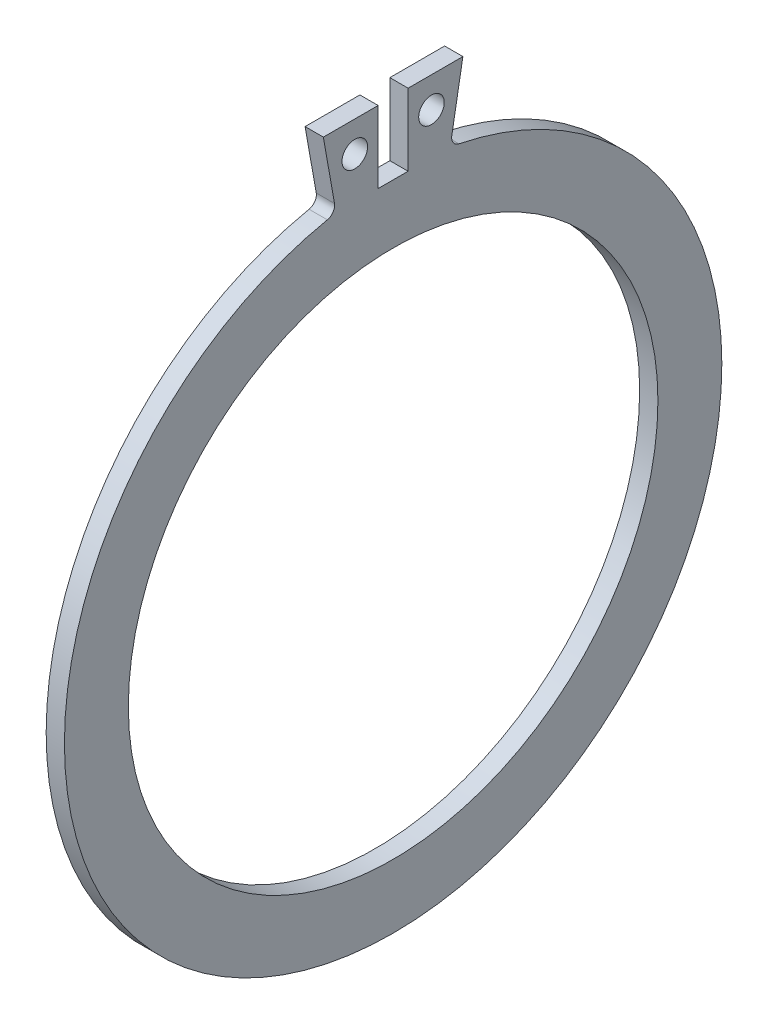
SolidWorks part; units mm, degrees
ref_plane "前视基准面" through (0, 0, 0) normal (0, 0, 1) x (1, 0, 0)
ref_plane "上视基准面" through (0, 0, 0) normal (0, 1, 0) x (1, 0, 0)
ref_plane "右视基准面" through (0, 0, 0) normal (1, 0, 0) x (0, 0, -1)
sketch "草图1" plane through (0, 0, 0) normal (1, 0, 0) x (0, 0, -1)
  line L0 (-3.2113, 18.2123) -> (-3.8203, 21.6658)
  line L1 (-3.8203, 21.6658) -> (-0.8203, 21.6658)
  line L2 (-0.8203, 21.6658) -> (-0.8203, 17.7265)
  line L4 (0, 0) -> (0, 22.6274) construction
  line L6 (0.8203, 21.6658) -> (0.8203, 17.7265)
  line L7 (3.8203, 21.6658) -> (0.8203, 21.6658)
  line L8 (3.2113, 18.2123) -> (3.8203, 21.6658)
  line L9 (-0.8203, 17.7265) -> (0.8203, 17.7265)
  circle A0 centre (0, 0) radius 14.5
  arc A1 (-3.6036, 17.6356) -> (3.6036, 17.6356) centre (0, 0) ccw
  circle A2 centre (-2.1, 20) radius 0.7
  circle A3 centre (2.1, 20) radius 0.7
  arc A4 (-3.6036, 17.6356) -> (-3.2113, 18.2123) centre (-3.7037, 18.1255) ccw
  arc A5 (3.6036, 17.6356) -> (3.2113, 18.2123) centre (3.7037, 18.1255) cw
  dimension "D1" = 0.5
  dimension "D2" = 0.5
extrude "凸台-拉伸1" add sketch "草图1" along normal blind 1
